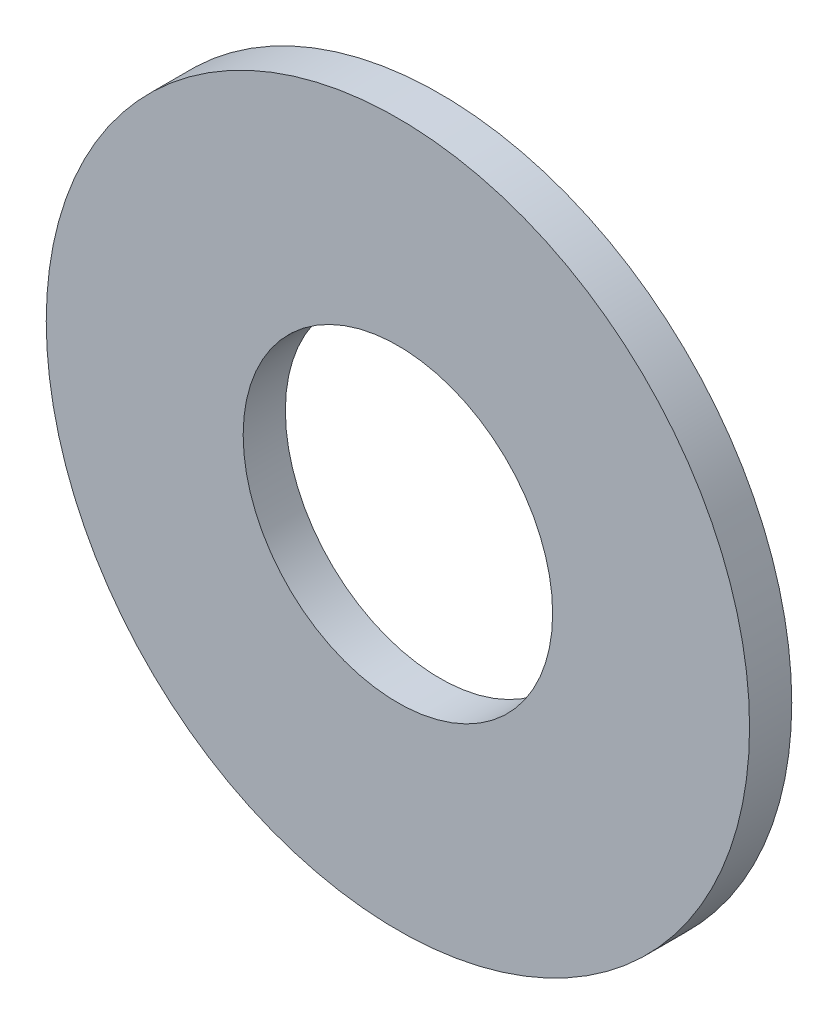
SolidWorks part; units mm, degrees
material "AISI 4340 Steel, normalized"
ref_plane "Front Plane" through (0, 0, 0) normal (0, 0, 1) x (1, 0, 0)
ref_plane "Top Plane" through (0, 0, 0) normal (0, 1, 0) x (1, 0, 0)
ref_plane "Right Plane" through (0, 0, 0) normal (1, 0, 0) x (0, 0, -1)
sketch "Sketch1" plane through (0, 0, 0) normal (0, 0, 1) x (1, 0, 0)
  circle A0 centre (0, 0) radius 2.5
  circle A1 centre (0, 0) radius 1.1
extrude "Washer_Envelope" add sketch "Sketch1" along normal blind 0.3
